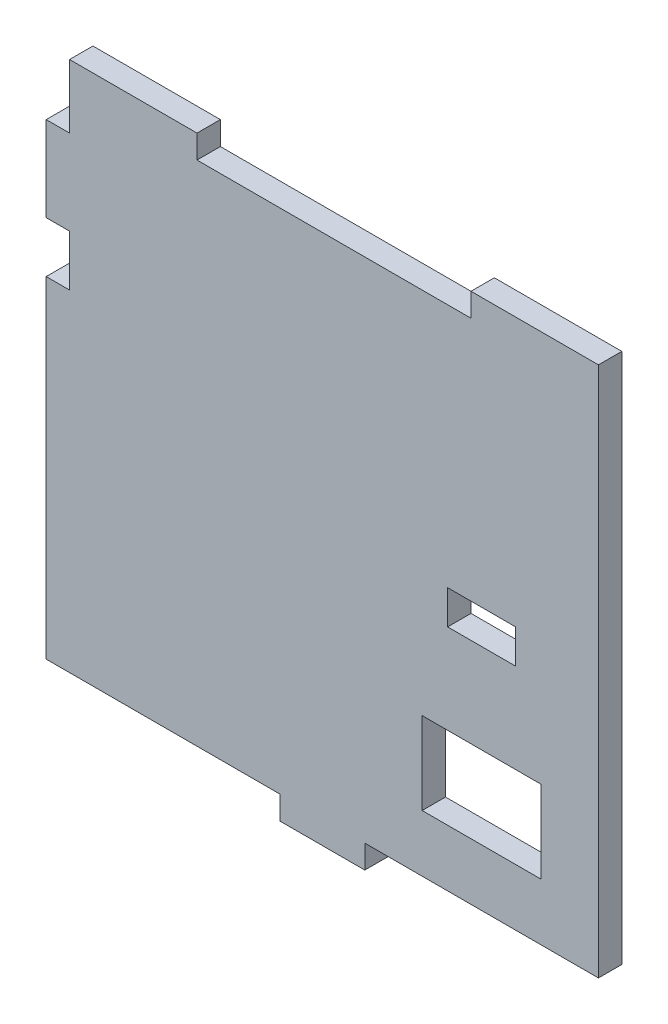
SolidWorks part; units mm, degrees
ref_plane "Alzado" through (0, 0, 0) normal (0, 0, 1) x (1, 0, 0)
ref_plane "Planta" through (0, 0, 0) normal (0, 1, 0) x (1, 0, 0)
ref_plane "Vista lateral" through (0, 0, 0) normal (1, 0, 0) x (0, 0, -1)
sketch "Croquis1" plane through (0, 0, 0) normal (0, 0, 1) x (1, 0, 0)
  line L0 (468.0164, 88.6082) -> (468.0164, -36.3918)
  line L1 (338.0164, -36.3918) -> (393.0164, -36.3918)
  line L2 (343.5164, 88.6082) -> (373.5164, 88.6082)
  line L3 (413.0164, -41.8918) -> (393.0164, -41.8918)
  line L4 (393.0164, -41.8918) -> (393.0164, -36.3918)
  line L5 (413.0164, -41.8918) -> (413.0164, -36.3918)
  line L6 (413.0164, -36.3918) -> (468.0164, -36.3918)
  line L7 (438.0164, 83.1082) -> (373.5164, 83.1082)
  line L8 (373.5164, 83.1082) -> (373.5164, 88.6082)
  line L9 (438.0164, 88.6082) -> (373.5164, 88.6082) construction
  line L10 (426.5164, -3.65) -> (454.5164, -3.65)
  line L11 (432.5164, 25.4332) -> (448.5164, 25.4332)
  line L13 (448.5164, 25.4332) -> (448.5164, 17.4332)
  line L14 (343.5164, 53.6082) -> (343.5164, 41.6082)
  line L15 (448.5164, 17.4332) -> (432.5164, 17.4332)
  line L16 (432.5164, 17.4332) -> (432.5164, 25.4332)
  line L19 (426.5164, -3.65) -> (426.5164, -23)
  line L20 (426.5164, -23) -> (454.5164, -23)
  line L21 (454.5164, -23) -> (454.5164, -3.65)
  line L22 (338.0164, 41.6082) -> (338.0164, -36.3918)
  line L44 (438.0164, 83.1082) -> (438.0164, 88.6082)
  line L46 (343.5164, 41.6082) -> (338.0164, 41.6082)
  line L47 (438.0164, 88.6082) -> (468.0164, 88.6082)
  line L55 (343.5164, 73.6082) -> (343.5164, 88.6082)
  line L56 (338.0164, 73.6082) -> (343.5164, 73.6082)
  line L57 (338.0164, 73.6082) -> (338.0164, 53.6082)
  line L58 (338.0164, 53.6082) -> (343.5164, 53.6082)
  point P22 (448.5164, 21.4332)
  dimension "D1" = 20
  dimension "D2" = 130
  dimension "D3" = 125
  dimension "D4" = 19.35
  dimension "D5" = 15
  dimension "D6" = 12
  dimension "D7" = 28
  dimension "D8" = 20
  dimension "D9" = 30
  dimension "D10" = 30
  dimension "D12" = 16
  dimension "D13" = 6
  dimension "D14" = 13.5
extrude "Saliente-Extruir1" add sketch "Croquis1" along normal blind 5.5
